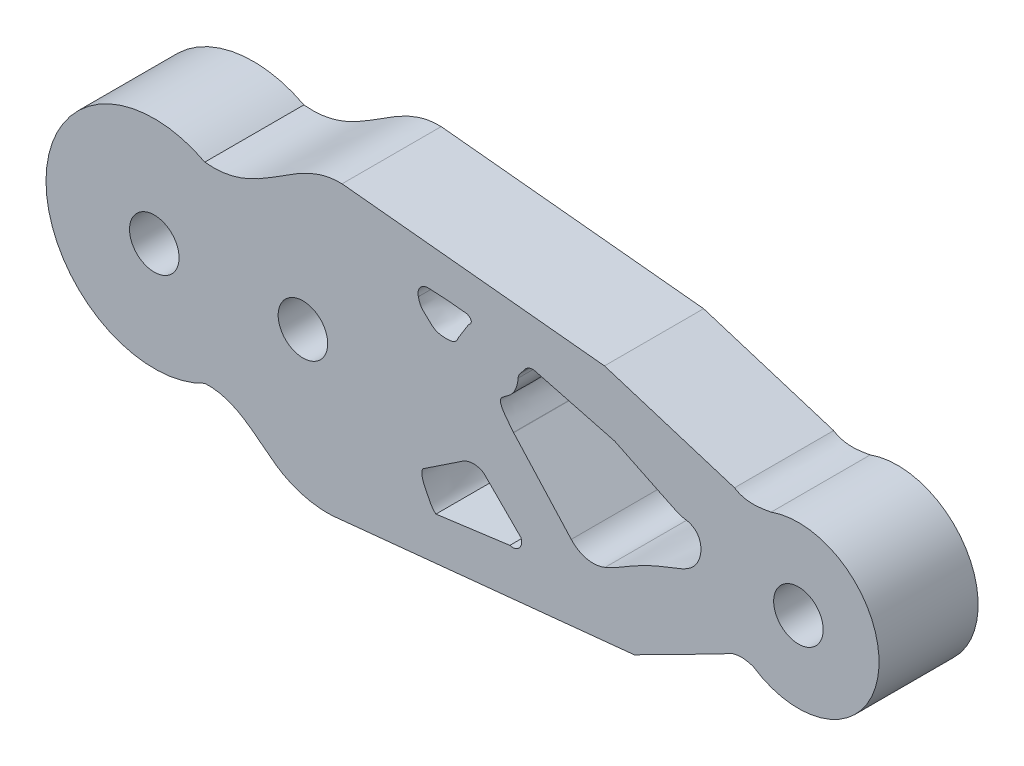
SolidWorks part; units mm, degrees
ref_plane "Front Plane" through (0, 0, 0) normal (0, 0, 1) x (1, 0, 0)
ref_plane "Top Plane" through (0, 0, 0) normal (0, 1, 0) x (1, 0, 0)
ref_plane "Right Plane" through (0, 0, 0) normal (1, 0, 0) x (0, 0, -1)
sketch "Sketch1" plane through (0, 0, 0) normal (0, 0, 1) x (1, 0, 0)
  line L0 (1.3706, 14.9583) -> (51.0041, 9.9495)
  line L1 (1.3706, -14.9583) -> (51.0041, -9.9495)
  line L2 (-15.0209, 15) -> (0, 15.021)
  line L3 (-15, -15) -> (-0.7932, -15)
  circle A0 centre (-15, 0) radius 2.5
  circle A1 centre (0, 0) radius 2.5
  circle A2 centre (50, 0) radius 2.5
  arc A4 (-15.0209, 15) -> (-15, -15) centre (-15, 0) ccw
  arc A5 (51.0041, -9.9495) -> (51.0041, 9.9495) centre (50, 0) ccw
  arc A6 (-0.7932, -15) -> (1.3706, -14.9583) centre (0, 0) ccw
  arc A7 (1.3706, 14.9583) -> (0, 15.021) centre (0, 0) ccw
  dimension "D1" = 20
  dimension "D2" = 15
  dimension "D4" = 5
  dimension "D5" = 5
  dimension "D3" = 50
  dimension "D6" = 15
extrude "Boss-Extrude1" add sketch "Sketch1" along normal mid plane 10
sketch "Sketch2" plane through (0, 0, 0) normal (0, 0, 1) x (1, 0, 0)
  line L0 (50, -1000) -> (50, 49000) construction
  line L1 (-15, -1000) -> (-15, 49000) construction
sketch "Sketch3" plane through (0, 0, 0) normal (0, 0, 1) x (1, 0, 0)
  line L0 (51.0041, 9.9495) -> (1.3706, 14.9583) construction
  line L1 (1.3706, -14.9583) -> (51.0041, -9.9495) construction
  line L2 (3.9499, 14.698) -> (3.9499, 23.599)
  line L3 (3.9499, 23.599) -> (-33.0984, 23.599)
  line L4 (-33.0984, 23.599) -> (-33.0984, -19.3341)
  line L5 (-33.0984, -19.3341) -> (3.0117, -19.3341)
  line L6 (3.0117, -19.3341) -> (3.0117, -14.7927)
  line L7 (22.5159, 8.3136) -> (31.4696, 5.9632)
  line L8 (31.4696, 5.9632) -> (38.1849, 2.7175)
  line L9 (28.289, -6.1533) -> (21.2552, 1.6112)
  line L10 (12.062, -6.1533) -> (16.0976, -3.4692)
  line L11 (18.2297, -3.4192) -> (21.9757, -7.1651)
  line L12 (13.422, -9.429) -> (20.8814, -8.4313)
  line L13 (11.4379, 10.0141) -> (14.6876, 9.8319)
  line L14 (14.6876, 9.8319) -> (16.2061, 9.6669)
  line L15 (16.7073, 8.7689) -> (15.6746, 7.0985)
  line L16 (30.4292, 12.0258) -> (43.5484, 7.9337)
  line L17 (30.4292, 19.7264) -> (61.7184, 19.7264)
  line L18 (30.4292, 19.7264) -> (30.4292, 12.0258)
  line L19 (30.4292, -17.8524) -> (61.7184, -17.8524)
  line L20 (61.7184, 19.7264) -> (61.7184, -17.8524)
  line L21 (30.4292, -13.2464) -> (42.4049, -7.1651)
  line L22 (30.4292, -13.2464) -> (30.4292, -17.8524)
  arc A0 (-9.9036, 9.6669) -> (-9.9036, -9.6669) centre (-15, 0) ccw
  arc A1 (18.2297, -3.4192) -> (16.0976, -3.4692) centre (17.2032, -5.1314) ccw
  arc A2 (20.8814, -8.4313) -> (21.9757, -7.1651) centre (21.1597, -7.5659) ccw
  arc A3 (45.4924, -6.7727) -> (47.2449, 7.6549) centre (50, 0) ccw
  spline S0 degree 3 poles (-9.9036, 9.6669) (-6.6521, 9.3201) (-2.5752, 12.1807) (1.7399, 14.763) (3.9499, 14.698) knots 0 0 0 0 0.582392 1 1 1 1
  spline S1 degree 3 poles (-9.9036, -9.6669) (-7.4765, -9.5332) (-5.1125, -11.3322) (-1.4199, -14.3078) (1.2483, -14.8931) (3.0117, -14.7927) knots 0 0 0 0 0.454121 0.625344 1 1 1 1
  spline S2 degree 3 poles (38.1849, 2.7175) (40.4644, 2.7256) (40.5673, -0.9319) (37.0228, -2.29) (33.1979, -3.7939) (30.5194, -5.9288) (28.289, -6.1533) knots 0 0 0 0 0.267175 0.422388 0.62445 1 1 1 1
  spline S3 degree 3 poles (21.729, 6.8238) (21.939, 7.3414) (22.4863, 7.3837) (22.5159, 8.3136) knots 0.760302 0.760302 0.760302 0.760302 1 1 1 1
  spline S4 degree 3 poles (21.2552, 1.6112) (18.0975, 5.3327) (21.5612, 3.1493) (21.729, 6.8238) knots 0 0 0 0 1 1 1 1
  spline S5 degree 3 poles (12.062, -6.1533) (11.8801, -6.849) (12.4954, -7.9277) (12.9664, -9.0639) (13.422, -9.429) knots 0 0 0 0 0.534202 1 1 1 1
  spline S6 degree 3 poles (16.2061, 9.6669) (16.6191, 9.734) (17.4081, 9.2716) (16.7073, 8.7689) knots 0 0 0 0 1 1 1 1
  spline S7 degree 3 poles (15.6746, 7.0985) (15.4967, 6.4682) (14.4965, 6.3574) (13.2341, 6.5645) (12.575, 7.3202) (11.8463, 7.9072) (11.593, 8.9011) (11.3809, 9.5826) (11.4379, 10.0141) knots 0 0 0 0 0.243008 0.400784 0.557347 0.677228 0.810823 1 1 1 1
  spline S8 degree 3 poles (43.5484, 7.9337) (44.668, 7.2245) (46.0283, 7.4264) (47.2449, 7.6549) knots 0 0 0 0 1 1 1 1
  spline S9 degree 2 poles (42.4049, -7.1651) (43.7913, -6.1258) (45.4924, -6.7727) knots 0 0 0 1 1 1
extrude "Cut-Extrude1" cut sketch "Sketch3" against normal through all both and the other way through all contours S1 A0 S0 L2 L3 L4 L5 L6 | L12 A2 L11 A1 L10 S5 | S7 L13 L14 S6 L15 | S3 L7 L8 S2 L9 S4 | A3 S8 L16 L18 L17 L20 L19 L22 L21 S9
fillet "Fillet_1mm" radius 1 9 edges at (14.6876, 9.8319, 0) (11.4379, 10.0141, 0) (21.2552, 1.6112, 0) (31.4696, 5.9632, 0) (22.5159, 8.3136, 0) (21.729, 6.8238, 0) (15.6746, 7.0985, 0) (16.7073, 8.7689, 0) (16.2061, 9.6669, 0)
fillet "Fillet_3mm" radius 3 2 edges at (28.289, -6.1533, 0) (38.1849, 2.7175, 0)
